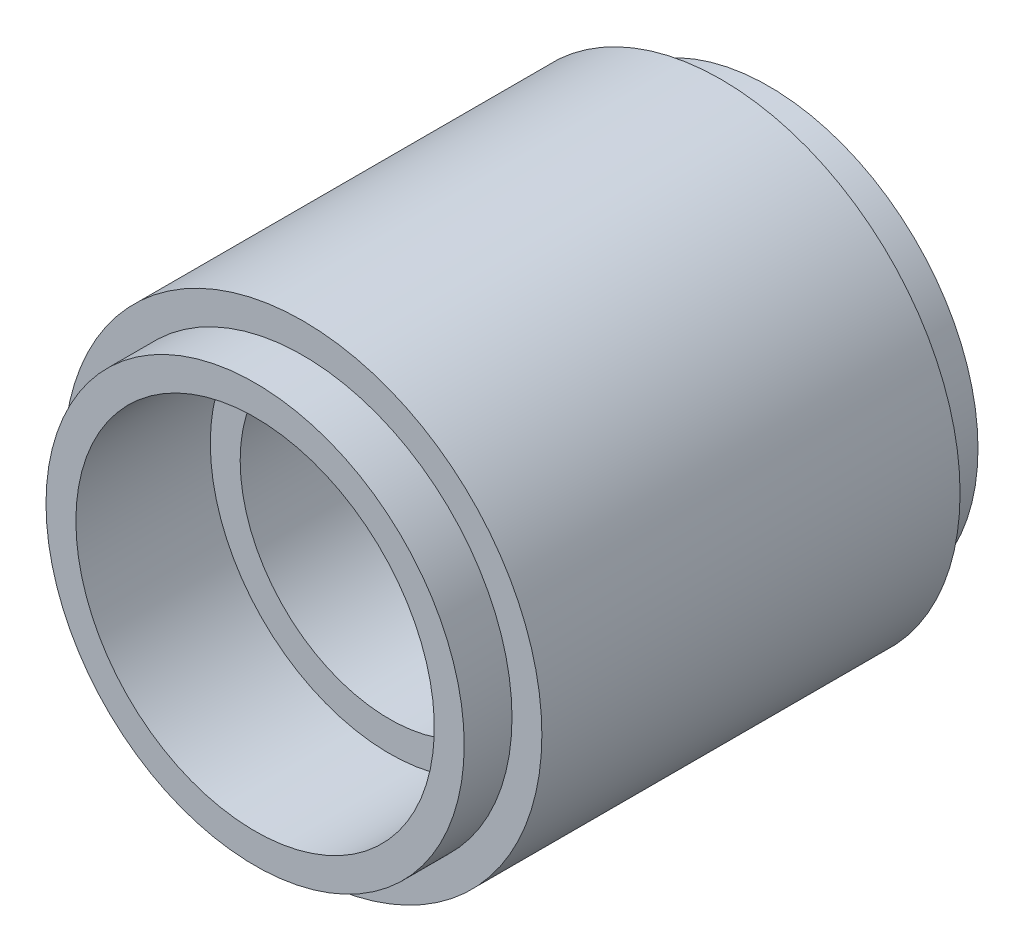
SolidWorks part; units mm, degrees
material "AISI 1020"
ref_plane "Front Plane" through (0, 0, 0) normal (0, 0, 1) x (1, 0, 0)
ref_plane "Top Plane" through (0, 0, 0) normal (0, 1, 0) x (1, 0, 0)
ref_plane "Right Plane" through (0, 0, 0) normal (1, 0, 0) x (0, 0, -1)
sketch "Sketch1" plane through (0, 0, 0) normal (1, 0, 0) x (0, 0, -1)
  line L0 (-11.1125, 12.7) -> (11.1125, 12.7)
  line L1 (11.1125, 12.7) -> (11.1125, 11.1125)
  line L2 (11.1125, 11.1125) -> (13.6525, 11.1125)
  line L3 (13.6525, 11.1125) -> (13.6525, 9.525)
  line L4 (13.6525, 9.525) -> (6.5088, 9.525)
  line L5 (6.5088, 9.525) -> (6.5088, 7.9375)
  line L6 (6.5088, 7.9375) -> (-6.5088, 7.9375)
  line L7 (-6.5088, 7.9375) -> (-6.5088, 9.525)
  line L8 (-6.5088, 9.525) -> (-13.6525, 9.525)
  line L9 (-13.6525, 9.525) -> (-13.6525, 11.1125)
  line L10 (-13.6525, 11.1125) -> (-11.1125, 11.1125)
  line L11 (-11.1125, 11.1125) -> (-11.1125, 12.7)
  line L12 (12.1833, 0) -> (-12.1833, 0) construction
  point P12 (0, 7.9375)
  point P13 (0, 12.7)
  point P19 (0, 0)
  dimension "D1" = 2.54
  dimension "D2" = 2.54
  dimension "D3" = 22.225
  dimension "D4" = 12.7
  dimension "D5" = 7.9375
  dimension "D6" = 7.1437
  dimension "D7" = 9.525
  dimension "D8" = 11.1125
revolve "Revolve1" add sketch "Sketch1" angle 360 about L12
equation "\"D2@Sketch1\"= \"D1@Sketch1\""
